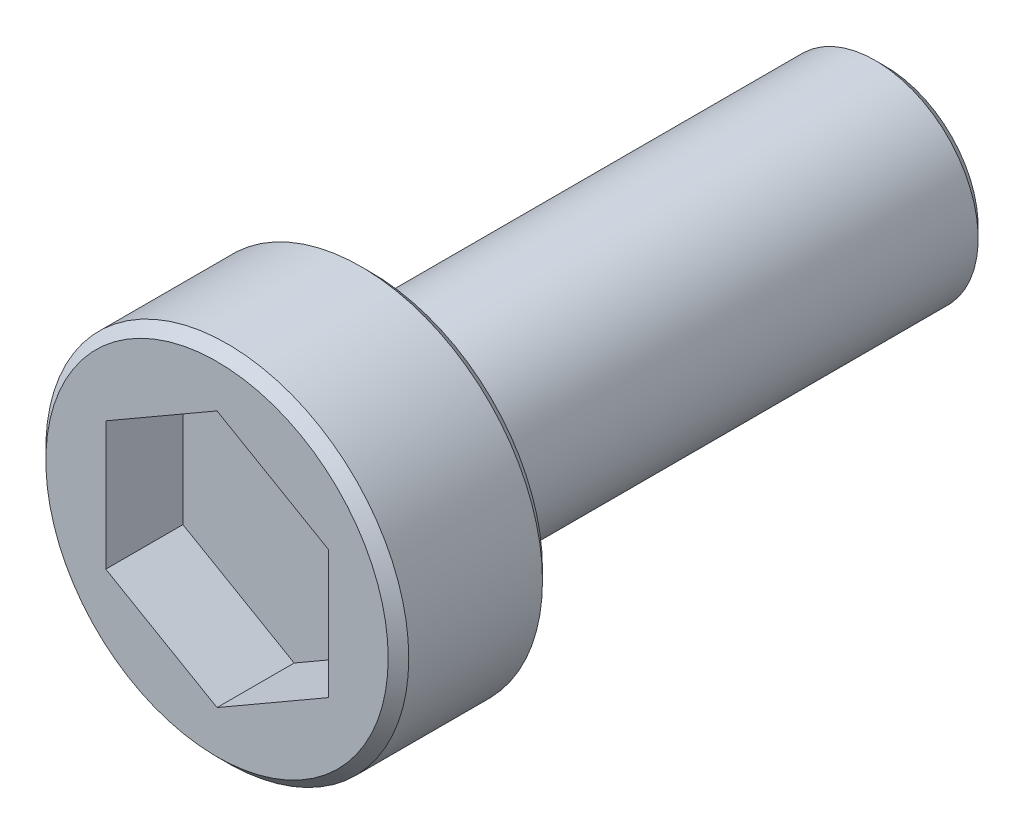
SolidWorks part; units mm, degrees
ref_plane "前视基准面" through (0, 0, 0) normal (0, 0, 1) x (1, 0, 0)
ref_plane "上视基准面" through (0, 0, 0) normal (0, 1, 0) x (1, 0, 0)
ref_plane "右视基准面" through (0, 0, 0) normal (1, 0, 0) x (0, 0, -1)
sketch "草图1" plane through (0, 0, 0) normal (0, 0, 1) x (1, 0, 0)
  circle A0 centre (0, 0) radius 2
extrude "凸台-拉伸1" add sketch "草图1" along normal blind 16
sketch "草图2" plane through (0, 0, 16) normal (0, 0, 1) x (1, 0, 0)
  circle A0 centre (0, 0) radius 3.5285
extrude "凸台-拉伸3" add sketch "草图2" along normal blind 3
sketch "草图3" plane through (0, 0, 19) normal (0, 0, 1) x (1, 0, 0)
  line L1 (0, 2.4977) -> (-2.1631, 1.2488)
  line L2 (-2.1631, 1.2488) -> (-2.1631, -1.2488)
  line L3 (-2.1631, -1.2488) -> (0, -2.4977)
  line L4 (0, -2.4977) -> (2.1631, -1.2488)
  line L5 (2.1631, -1.2488) -> (2.1631, 1.2488)
  line L6 (2.1631, 1.2488) -> (0, 2.4977)
  circle A0 centre (0, 0) radius 2.1631 construction
extrude "切除-拉伸2" cut sketch "草图3" against normal blind 1.5
chamfer "倒角1" distance 0.2 angle 45 1 edges at (2, 0, 0)
chamfer "倒角2" distance 0.2 angle 45 2 edges at (3.5285, 0, 19) (3.5285, 0, 16)
sketch "草图4" plane through (0, 0, 0) normal (0, 0, -1) x (-1, 0, 0)
  circle A0 centre (0, 0) radius 2
extrude "切除-拉伸3" cut sketch "草图4" against normal blind 6
chamfer "倒角3" distance 0.2 angle 45 1 edges at (-2, 0, 6)
